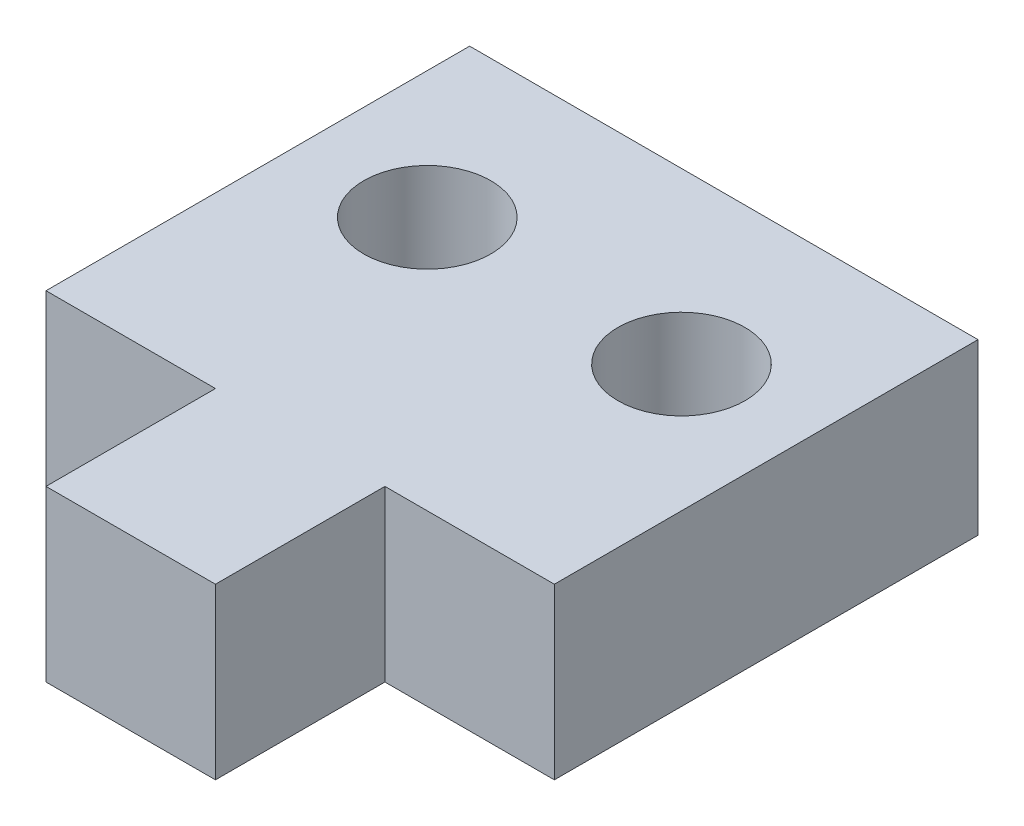
SolidWorks part; units mm, degrees
ref_plane "Front Plane" through (0, 0, 0) normal (0, 0, 1) x (1, 0, 0)
ref_plane "Top Plane" through (0, 0, 0) normal (0, 1, 0) x (1, 0, 0)
ref_plane "Right Plane" through (0, 0, 0) normal (1, 0, 0) x (0, 0, -1)
sketch "Sketch1" plane through (0, 0, 0) normal (0, 1, 0) x (1, 0, 0)
  line L0 (-2, -5) -> (-2, -9)
  line L1 (-6, 5) -> (6, 5)
  line L2 (-6, 5) -> (-6, -5)
  line L3 (-6, -5) -> (6, -5)
  line L4 (6, 5) -> (6, -5)
  line L5 (-6, 5) -> (6, -5) construction
  line L6 (-6, -5) -> (6, 5) construction
  line L7 (-2, -9) -> (2, -9)
  line L8 (2, -9) -> (2, -5)
  point P0 (0, 0)
  point P9 (0, -9)
  point P11 (0, -5)
  dimension "D1" = 12
  dimension "D2" = 10
  dimension "D3" = 4
  dimension "D4" = 4
extrude "Boss-Extrude1" add sketch "Sketch1" along normal blind 4 contours L4 L1 L2 L3 | L7 L8 L3 L0
sketch "Sketch2" plane through (0, 4, 0) normal (0, 1, 0) x (1, 0, 0)
  line L0 (-3, 1) -> (3, 1) construction
  line L2 (-6, 5) -> (6, 5) construction
  circle A0 centre (-3, 1) radius 1.5
  circle A1 centre (3, 1) radius 1.5
  point P4 (0, 0)
  point P5 (0, 1)
  point P9 (3.5903, 1)
  dimension "D2" = 3
  dimension "D1" = 6
  dimension "D3" = 4
extrude "Cut-Extrude1" cut sketch "Sketch2" against normal through all
